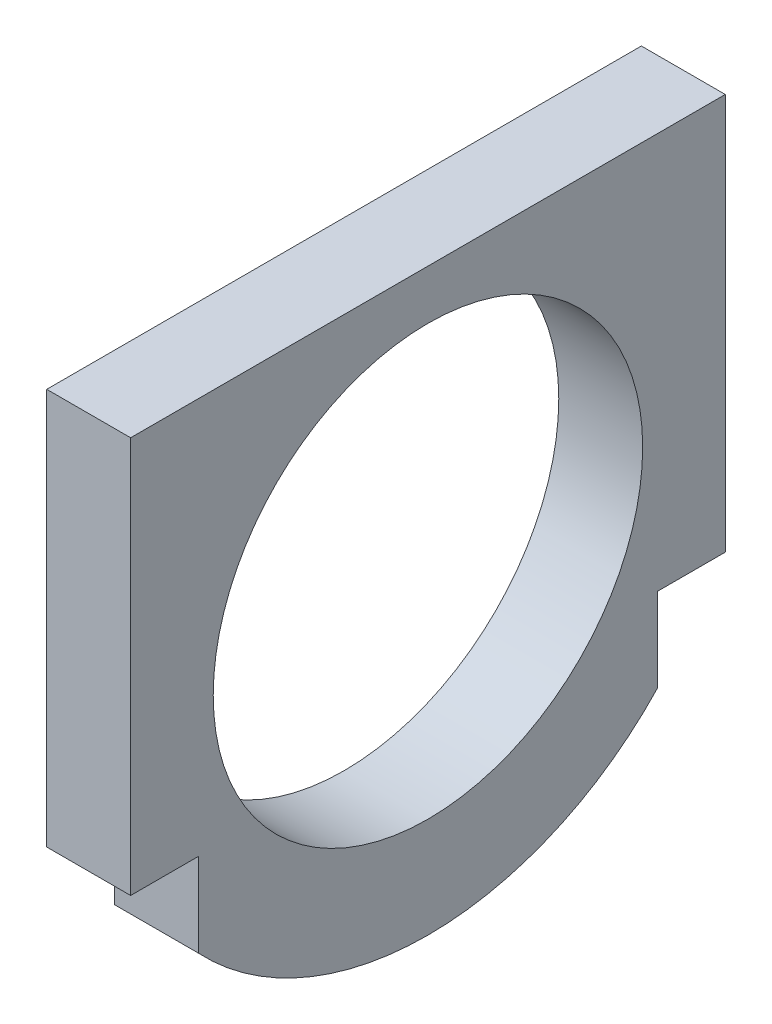
SolidWorks part; units mm, degrees
ref_plane "Front Plane" through (0, 0, 0) normal (0, 0, 1) x (1, 0, 0)
ref_plane "Top Plane" through (0, 0, 0) normal (0, 1, 0) x (1, 0, 0)
ref_plane "Right Plane" through (0, 0, 0) normal (1, 0, 0) x (0, 0, -1)
sketch "Sketch1" plane through (0, 0, 0) normal (1, 0, 0) x (0, 0, -1)
  line L0 (9, -4) -> (9, 8)
  line L1 (9, 8) -> (-9, 8)
  line L2 (-9, 8) -> (-9, -4)
  line L5 (6.9455, -6.54) -> (6.9455, -4)
  line L6 (6.9455, -4) -> (9, -4)
  line L7 (-6.9455, -6.54) -> (-6.9455, -4)
  line L8 (-9, -4) -> (-6.9455, -4)
  circle A0 centre (0, 0) radius 6.5
  arc A1 (-6.9455, -6.54) -> (6.9455, -6.54) centre (0, 0) ccw
  dimension "D1" = 13
  dimension "D6" = 9.54
  dimension "D2" = 12
  dimension "D3" = 8
  dimension "D4" = 9
  dimension "D5" = 9
  dimension "D7" = 2.54
extrude "Base" add sketch "Sketch1" along normal blind 2.54
